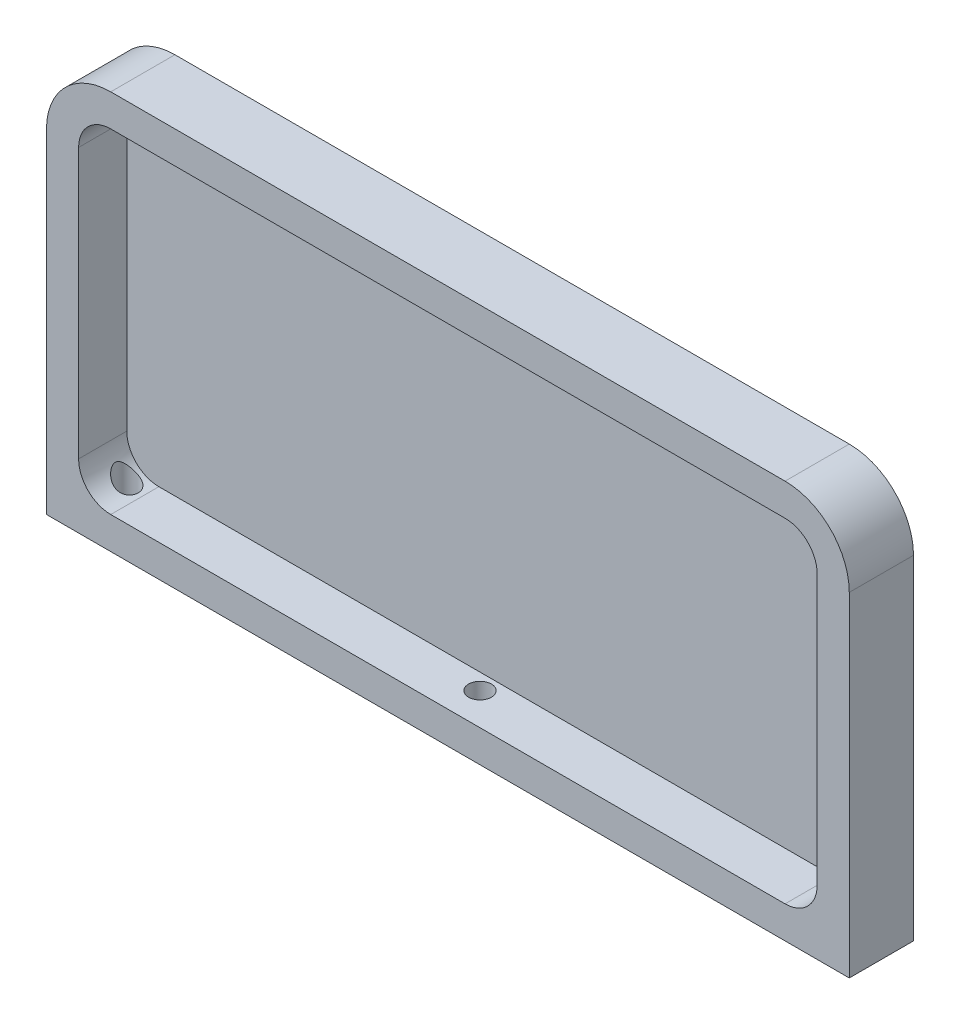
SolidWorks part; units mm, degrees
material "ABS PC"
ref_plane "Front Plane" through (0, 0, 0) normal (0, 0, 1) x (1, 0, 0)
ref_plane "Top Plane" through (0, 0, 0) normal (0, 1, 0) x (1, 0, 0)
ref_plane "Right Plane" through (0, 0, 0) normal (1, 0, 0) x (0, 0, -1)
sketch "Sketch1" plane through (0, 0, 0) normal (0, 0, 1) x (1, 0, 0)
  line L1 (-39.6875, -19.685) -> (39.6875, -19.685)
  line L2 (-39.6875, -19.685) -> (-39.6875, 19.685)
  line L3 (-39.6875, 19.685) -> (39.6875, 19.685)
  line L4 (39.6875, -19.685) -> (39.6875, 19.685)
  line L5 (-39.6875, -19.685) -> (39.6875, 19.685) construction
  line L6 (-39.6875, 19.685) -> (39.6875, -19.685) construction
  point P0 (0, 0)
  dimension "D1" = 39.37
  dimension "D2" = 79.375
extrude "Boss-Extrude1" add sketch "Sketch1" along normal blind 6.35
fillet "Fillet1" radius 6.35 2 edges at (39.6875, 19.685, 3.175) (-39.6875, 19.685, 3.175)
hole_wizard "#4-40 Tapped Hole1" positions "Sketch3" profile "Sketch4" tap size "#4-40" standard "Ansi Inch"
sketch "Sketch3" plane through (0, -19.685, 0) normal (0, -1, 0) x (1, 0, 0)
  line L0 (-39.6875, 3.175) -> (39.6875, 3.175) construction
  line L1 (-39.6875, 6.35) -> (-39.6875, 0) construction
  line L2 (39.6875, 6.35) -> (39.6875, 0) construction
  point P0 (0, 3.175)
  point P10 (-34.925, 3.175)
  point P12 (34.925, 3.175)
  dimension "D1" = 34.925
  dimension "D2" = 34.925
sketch "Sketch4" plane through (0, -19.685, 3.175) normal (1, 0, 0) x (0, 0, -1)
  line L0 (0, 0) -> (0, 8.2992)
  line L1 (0, 8.2992) -> (1.1303, 7.62)
  line L2 (1.1303, 7.62) -> (1.1303, 0)
  line L5 (1.1303, 0) -> (0, 0)
  line L10 (0, 8.2992) -> (-1.1303, 7.62) construction
  line L11 (0, -6.35) -> (0, 107.95) construction
  dimension "Tap Drill Dia." = 2.2606
  dimension "Tap Drill Depth" = 7.62
  dimension "Drill Angle" = 118
cosmetic thread "Hole Thread1" parameters "D1"=5.588, "D2"=2.8448
cosmetic thread "Hole Thread2" parameters "D1"=5.588, "D2"=2.8448
cosmetic thread "Hole Thread3" parameters "D1"=5.588, "D2"=2.8448
sketch "Sketch5" plane through (0, 0, 6.35) normal (0, 0, 1) x (1, 0, 0)
  line L8 (36.5125, -16.51) -> (36.5125, 13.335)
  line L9 (33.3375, 16.51) -> (-33.3375, 16.51)
  line L10 (-36.5125, 13.335) -> (-36.5125, -16.51)
  line L11 (-36.5125, -16.51) -> (36.5125, -16.51)
  line L12 (36.5125, -13.335) -> (36.5125, 13.335)
  line L13 (33.3375, 16.51) -> (-33.3375, 16.51)
  line L14 (-36.5125, 13.335) -> (-36.5125, -13.335)
  line L15 (-33.3375, -16.51) -> (33.3375, -16.51)
  arc A0 (36.5125, -13.335) -> (33.3375, -16.51) centre (33.3375, -13.335) cw
  arc A1 (-36.5125, -13.335) -> (-33.3375, -16.51) centre (-33.3375, -13.335) ccw
  arc A4 (36.5125, 13.335) -> (33.3375, 16.51) centre (33.3375, 13.335) ccw
  arc A5 (-33.3375, 16.51) -> (-36.5125, 13.335) centre (-33.3375, 13.335) ccw
  arc A6 (36.5125, 13.335) -> (33.3375, 16.51) centre (33.3375, 13.335) ccw
  arc A7 (-33.3375, 16.51) -> (-36.5125, 13.335) centre (-33.3375, 13.335) ccw
  dimension "D2" = 3.175
  dimension "D1" = 3.175
extrude "Cut-Extrude1" cut sketch "Sketch5" against normal blind 4.7625
